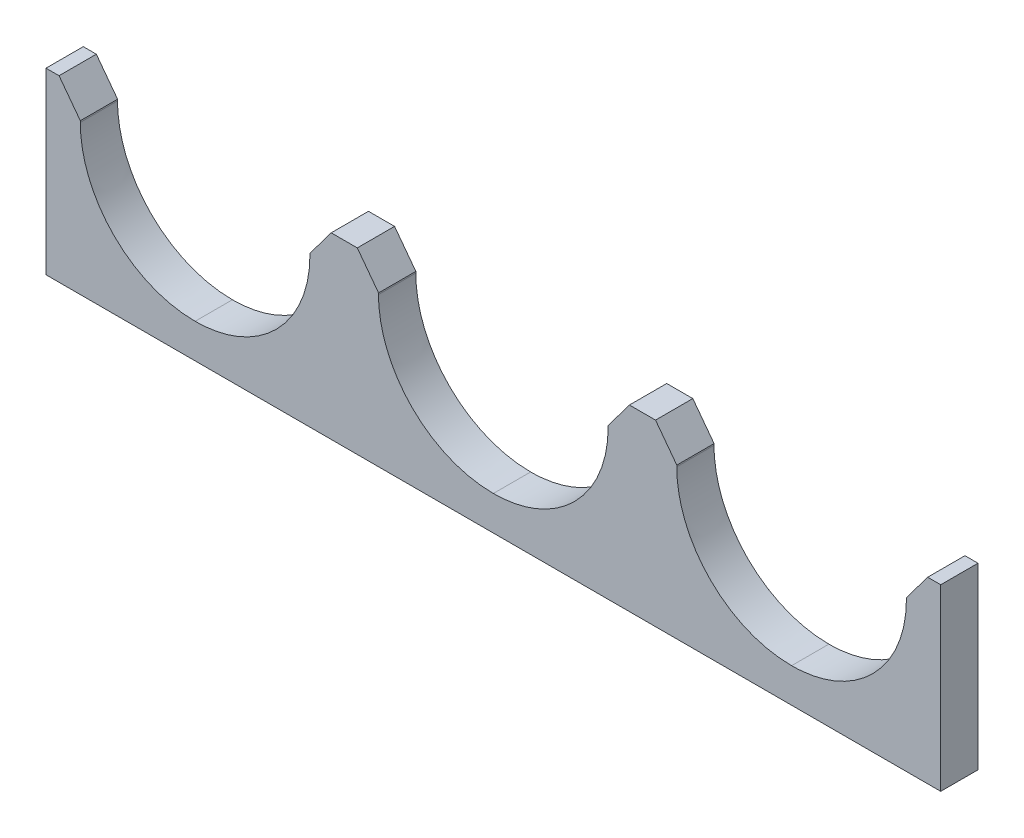
SolidWorks part; units mm, degrees
ref_plane "Plan de face" through (0, 0, 0) normal (0, 0, 1) x (1, 0, 0)
ref_plane "Plan de dessus" through (0, 0, 0) normal (0, 1, 0) x (1, 0, 0)
ref_plane "Plan de droite" through (0, 0, 0) normal (1, 0, 0) x (0, 0, -1)
sketch "Model" plane through (0, 0, 0) normal (0, 0, 1) x (1, 0, 0)
  line L0 (245.9874, -237.2413) -> (238.8578, -227.7328)
  line L1 (238.8578, -227.7328) -> (230.1045, -227.7328)
  line L2 (230.1045, -227.7328) -> (222.975, -237.2414)
  line L3 (145.9874, -237.2413) -> (138.8578, -227.7328)
  line L4 (138.8578, -227.7328) -> (130.1045, -227.7328)
  line L5 (130.1045, -227.7328) -> (122.975, -237.2414)
  line L6 (45.9874, -237.2413) -> (38.8578, -227.7328)
  line L7 (38.8578, -227.7328) -> (34.4812, -227.7328)
  line L8 (34.4812, -227.7328) -> (34.4812, -287.7328)
  line L9 (34.4812, -287.7328) -> (334.4812, -287.7328)
  line L10 (334.4812, -287.7328) -> (334.4812, -227.7328)
  line L11 (334.4812, -227.7328) -> (330.1046, -227.7328)
  line L12 (330.1046, -227.7328) -> (322.9749, -237.2414)
  spline S0 degree 3 poles (322.9749, -237.2414) (322.977, -237.4052) (322.9812, -237.5685) (322.9812, -237.7328) knots 0 0 0 0 1 1 1 1
  spline S1 degree 3 poles (322.9812, -237.7328) (322.9812, -258.9958) (305.7441, -276.2328) (284.4812, -276.2328) knots 1 1 1 1 2 2 2 2
  spline S2 degree 3 poles (284.4812, -276.2328) (263.2182, -276.2328) (245.9812, -258.9958) (245.9812, -237.7328) knots 2 2 2 2 3 3 3 3
  spline S3 degree 3 poles (245.9812, -237.7328) (245.9812, -237.5685) (245.9854, -237.4052) (245.9874, -237.2413) knots 3 3 3 3 4 4 4 4
  spline S4 degree 3 poles (222.975, -237.2414) (222.977, -237.4052) (222.9812, -237.5685) (222.9812, -237.7328) knots 7 7 7 7 8 8 8 8
  spline S5 degree 3 poles (222.9812, -237.7328) (222.9812, -258.9958) (205.7441, -276.2328) (184.4812, -276.2328) knots 8 8 8 8 9 9 9 9
  spline S6 degree 3 poles (184.4812, -276.2328) (163.2182, -276.2328) (145.9812, -258.9958) (145.9812, -237.7328) knots 9 9 9 9 10 10 10 10
  spline S7 degree 3 poles (145.9812, -237.7328) (145.9812, -237.5685) (145.9854, -237.4052) (145.9874, -237.2413) knots 10 10 10 10 11 11 11 11
  spline S8 degree 3 poles (122.975, -237.2414) (122.977, -237.4052) (122.9812, -237.5685) (122.9812, -237.7328) knots 14 14 14 14 15 15 15 15
  spline S9 degree 3 poles (122.9812, -237.7328) (122.9812, -258.9958) (105.7441, -276.2328) (84.4812, -276.2328) knots 15 15 15 15 16 16 16 16
  spline S10 degree 3 poles (84.4812, -276.2328) (63.2182, -276.2328) (45.9812, -258.9958) (45.9812, -237.7328) knots 16 16 16 16 17 17 17 17
  spline S11 degree 3 poles (45.9812, -237.7328) (45.9812, -237.5685) (45.9853, -237.4052) (45.9874, -237.2413) knots 17 17 17 17 18 18 18 18
extrude "Boss.-Extru.1" add sketch "Model" along normal blind 12.5
